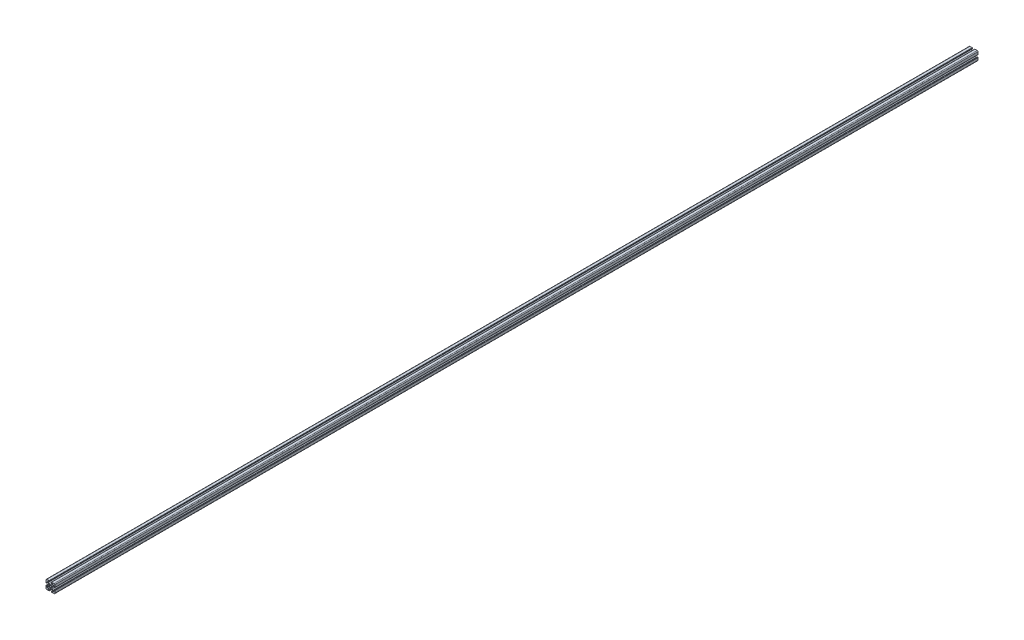
SolidWorks part; units mm, degrees
ref_plane "Front Plane" through (0, 0, 0) normal (0, 0, 1) x (1, 0, 0)
ref_plane "Top Plane" through (0, 0, 0) normal (0, 1, 0) x (1, 0, 0)
ref_plane "Right Plane" through (0, 0, 0) normal (1, 0, 0) x (0, 0, -1)
sketch "Sketch2" plane through (0, 0, 0) normal (0, 0, 1) x (1, 0, 0)
  line L0 (0, 10) -> (0, -10) construction
  line L1 (-10, 0) -> (10, 0) construction
  line L2 (2.5, -10) -> (10, -10)
  line L3 (10, -10) -> (10, -2.5)
  line L4 (2.5, -10) -> (2.5, -7.9246)
  line L5 (2.5, -7.9246) -> (6.4571, -7.9246)
  line L6 (6.4571, -7.9246) -> (2.1325, -3.6)
  line L7 (0, 0) -> (10, -10) construction
  line L8 (10, -2.5) -> (7.9246, -2.5)
  line L9 (7.9246, -2.5) -> (7.9246, -6.4571)
  line L10 (7.9246, -6.4571) -> (3.6, -2.1325)
  line L11 (5.7623, -4.2948) -> (4.2948, -5.7623) construction
  circle A0 centre (0, 0) radius 2.15
  arc A1 (5.25, -7.9246) -> (5.6036, -7.0711) centre (5.25, -7.4246) ccw construction
  point P8 (0, -3.6)
  point P16 (5.0286, -5.0286)
  dimension "Center Hole Diameter" = 4.3
  dimension "D3" = 0.5
  dimension "Rail Height" = 20
  dimension "Rail Width" = 20
  dimension "T-Slot Width" = 5
  dimension "Slot Depth" = 6.4
  dimension "Slot Inner Width" = 11.5
sketch "Sketch3" plane through (0, 0, 0) normal (1, 0, 0) x (0, 0, -1)
  line L0 (-76.2, -10) -> (76.2, -10) construction
  line L1 (-50.8, 0) -> (50.8, 0) construction
  line L2 (0, 10) -> (0, -10) construction
  line L3 (0, 10) -> (0, -10) construction
  point P6 (-50.8, 0)
  point P8 (50.8, 0)
  dimension "D1" = 25.4
  dimension "Length" = 152.4
sketch "Sketch4" plane through (0, 0, 0) normal (0, 0, 1) x (1, 0, 0)
  line L0 (3, -10) -> (8.25, -10)
  line L1 (2.5, -10) -> (10, -10) construction
  line L2 (2.5, -10) -> (2.5, -7.9246) construction
  line L3 (2.5, -7.9246) -> (6.4571, -7.9246) construction
  line L4 (2.5, -8.4246) -> (2.5, -9.5)
  line L5 (3, -7.9246) -> (5.25, -7.9246)
  line L6 (0, -3.6) -> (0.8898, -3.6)
  line L7 (6.4571, -7.9246) -> (2.1325, -3.6) construction
  line L8 (3.0112, -4.4787) -> (5.6036, -7.0711)
  line L9 (10, -10) -> (10, -2.5) construction
  line L10 (7.9246, -6.4571) -> (3.6, -2.1325) construction
  line L11 (7.9246, -2.5) -> (7.9246, -6.4571) construction
  line L12 (7.9246, -5.25) -> (7.9246, -3)
  line L13 (10, -2.5) -> (7.9246, -2.5) construction
  line L14 (8.4246, -2.5) -> (9.5, -2.5)
  line L15 (10, -3) -> (10, -8.25)
  line L16 (7.0711, -5.6036) -> (4.4787, -3.0112)
  line L17 (3.6, 0) -> (3.6, -0.8898)
  line L18 (-10, 0) -> (10, 0) construction
  line L19 (0, -3.6) -> (0, -2.15)
  line L20 (0, 10) -> (0, -10) construction
  line L21 (3.6, 0) -> (2.15, 0)
  arc A0 (2.5, -9.5) -> (3, -10) centre (3, -9.5) ccw
  arc A1 (5.25, -7.9246) -> (5.6036, -7.0711) centre (5.25, -7.4246) ccw construction
  arc A2 (2.5, -8.4246) -> (3, -7.9246) centre (3, -8.4246) cw
  arc A3 (5.25, -7.9246) -> (5.6036, -7.0711) centre (5.25, -7.4246) ccw
  arc A4 (0.8898, -3.6) -> (3.0112, -4.4787) centre (0.8898, -6.6) cw
  arc A5 (8.25, -10) -> (10, -8.25) centre (8.25, -8.25) ccw
  arc A6 (7.0711, -5.6036) -> (7.9246, -5.25) centre (7.4246, -5.25) ccw
  arc A7 (7.9246, -3) -> (8.4246, -2.5) centre (8.4246, -3) cw
  arc A8 (9.5, -2.5) -> (10, -3) centre (9.5, -3) cw
  arc A9 (4.4787, -3.0112) -> (3.6, -0.8898) centre (6.6, -0.8898) cw
  circle A10 centre (0, 0) radius 2.15 construction
  arc A11 (0, -2.15) -> (2.15, 0) centre (0, 0) ccw
  dimension "D1" = 1.75
  dimension "D2" = 3
extrude "Boss-Extrude1" add sketch "Sketch4" along normal mid plane 2100
mirror "Mirror1" about plane through (0, 0, 0) normal (1, 0, 0) of bodies 134
mirror "Mirror2" about plane through (0, 0, 0) normal (0, 1, 0) of bodies 135
equation "\"D3@Sketch2\"=\"T-Slot Width@Sketch2\"*0.1"
equation "\"D1@Sketch4\"=\"D3@Sketch2\"*3.5"
equation "\"D2@Sketch4\"=\"D3@Sketch2\"*6"
equation "\"D1@Boss-Extrude1\"=110"
